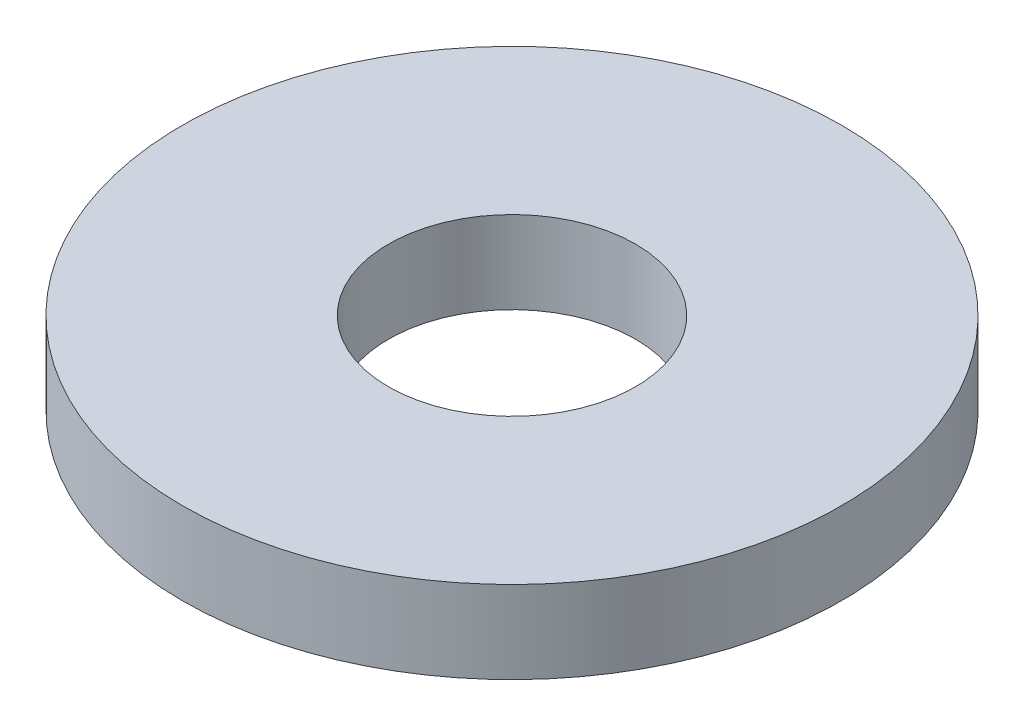
SolidWorks part; units mm, degrees
ref_plane "前视基准面" through (0, 0, 0) normal (0, 0, 1) x (1, 0, 0)
ref_plane "上视基准面" through (0, 0, 0) normal (0, 1, 0) x (1, 0, 0)
ref_plane "右视基准面" through (0, 0, 0) normal (1, 0, 0) x (0, 0, -1)
other "Configuration Table"
sketch "草图1" plane through (0, 0, 0) normal (0, 1, 0) x (1, 0, 0)
  circle A0 centre (0, 0) radius 4
  circle A1 centre (0, 0) radius 1.5
  point P4 (0, 0)
  dimension "D1" = 8
  dimension "D2" = 3
extrude "凸台-拉伸1" add sketch "草图1" along normal blind 1
